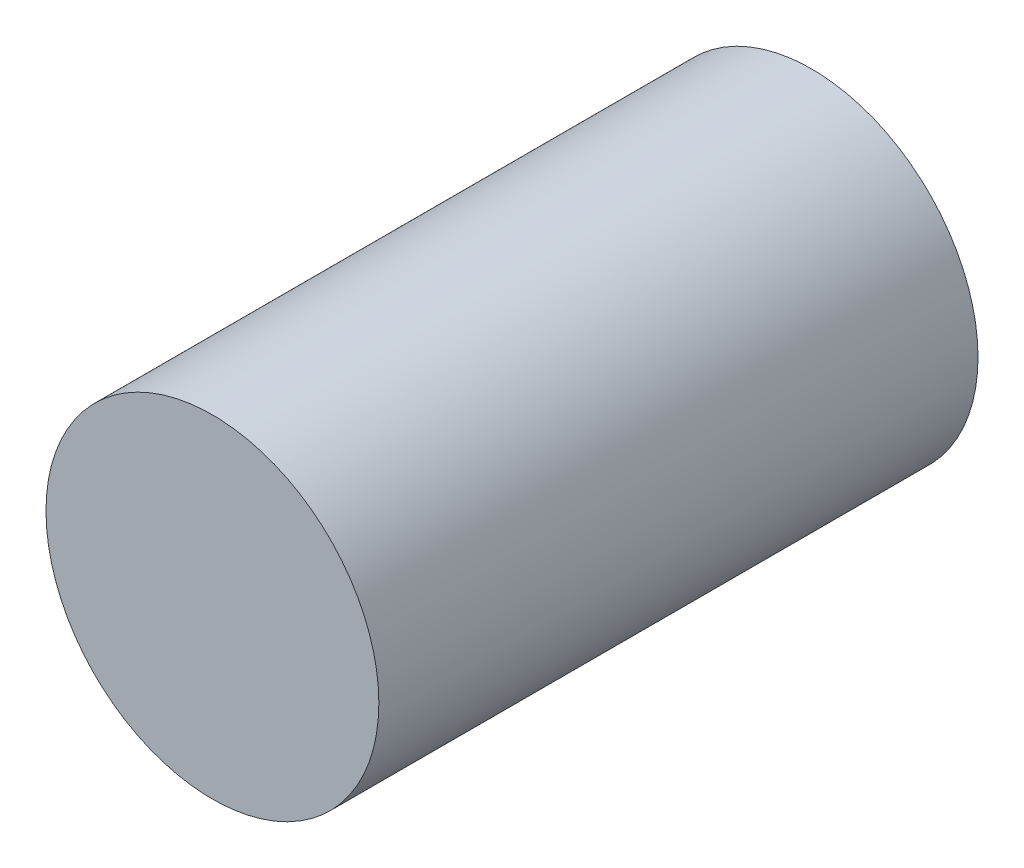
SolidWorks part; units mm, degrees
ref_plane "Front Plane" through (0, 0, 0) normal (0, 0, 1) x (1, 0, 0)
ref_plane "Top Plane" through (0, 0, 0) normal (0, 1, 0) x (1, 0, 0)
ref_plane "Right Plane" through (0, 0, 0) normal (1, 0, 0) x (0, 0, -1)
sketch "Sketch1" plane through (0, 0, 0) normal (0, 0, 1) x (1, 0, 0)
  circle A0 centre (0, 0) radius 63.5
  dimension "D1" = 127
extrude "Boss-Extrude1" add sketch "Sketch1" along normal mid plane 228.6
